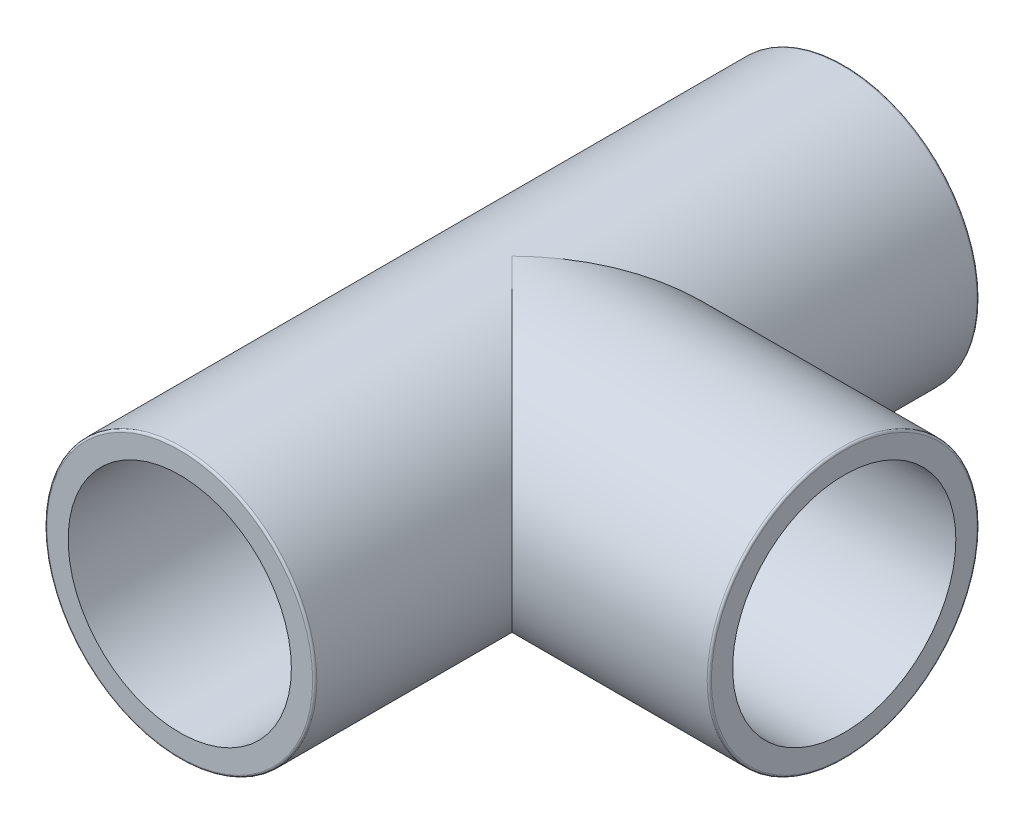
SolidWorks part; units mm, degrees
ref_plane "Front" through (0, 0, 0) normal (0, 0, 1) x (1, 0, 0)
ref_plane "Top" through (0, 0, 0) normal (0, 1, 0) x (1, 0, 0)
ref_plane "Right" through (0, 0, 0) normal (1, 0, 0) x (0, 0, -1)
sketch "Sketch2" plane through (0, 0, 0) normal (0, 0, 1) x (1, 0, 0)
  circle A0 centre (0, 0) radius 13
  circle A1 centre (0, 0) radius 10.25
  dimension "D1" = 26
  dimension "D2" = 20.5
extrude "Boss-Extrude1" add sketch "Sketch2" against normal blind 64
ref_plane "Plane1" through (32, 0, 0) normal (1, 0, 0) x (0, 0, -1)
sketch "Sketch3" plane through (32, 0, 0) normal (1, 0, 0) x (0, 0, -1)
  circle A0 centre (32, 0) radius 13
extrude "Boss-Extrude2" add sketch "Sketch3" against normal blind 32
sketch "Sketch4" plane through (32, 0, 0) normal (1, 0, 0) x (0, 0, -1)
  circle A0 centre (32, 0) radius 10.25
  dimension "D1" = 20.5
extrude "Cut-Extrude1" cut sketch "Sketch4" against normal blind 32
sketch "Sketch5" plane through (0, 0, 0) normal (0, 0, 1) x (1, 0, 0)
  circle A0 centre (0, 0) radius 10.25 construction
  circle A1 centre (0, 0) radius 10.25
extrude "Cut-Extrude2" cut sketch "Sketch5" against normal blind 78
sketch "Sketch6" plane through (0, 0, 0) normal (0, 0, 1) x (1, 0, 0)
  circle A0 centre (0, 0) radius 10.75
  dimension "D1" = 21.5
extrude "Cut-Extrude3" cut sketch "Sketch6" against normal blind 20
sketch "Sketch7" plane through (0, 0, -64) normal (0, 0, -1) x (-1, 0, 0)
  circle A0 centre (0, 0) radius 10.75
  dimension "D1" = 21.5
extrude "Cut-Extrude4" cut sketch "Sketch7" against normal blind 20
sketch "Sketch8" plane through (32, 0, 0) normal (1, 0, 0) x (0, 0, -1)
  circle A0 centre (32, 0) radius 10.75
  dimension "D1" = 21.5
extrude "Cut-Extrude5" cut sketch "Sketch8" against normal blind 20
fillet "Fillet1" radius 0.2 3 edges at (13, 0, -64) (13, 0, 0) (32, 0, -45)
